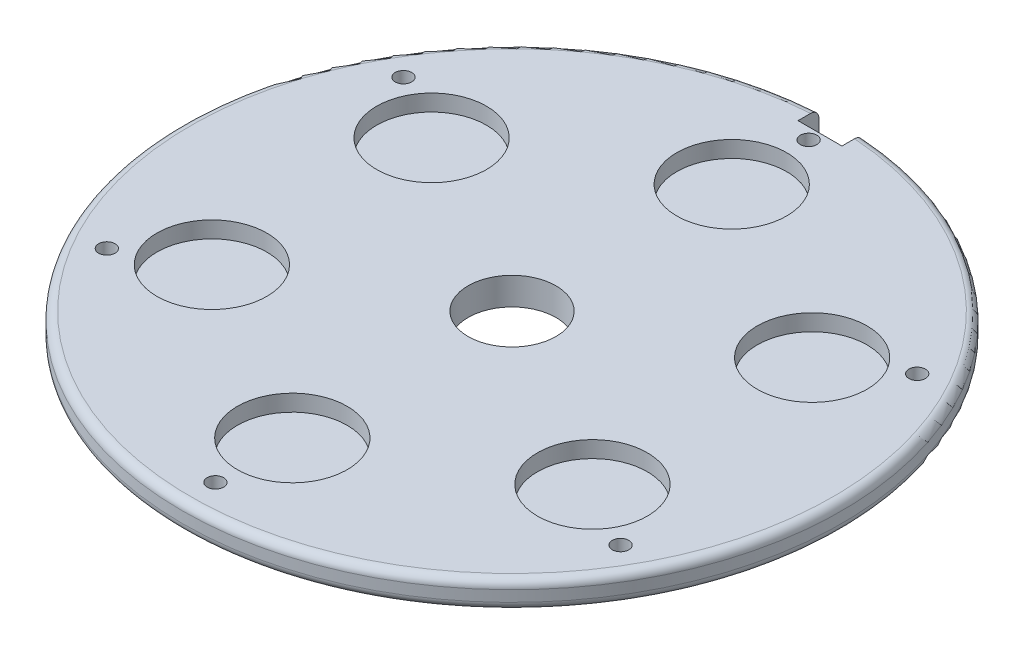
SolidWorks part; units mm, degrees
material "ABS"
ref_plane "Front Plane" through (0, 0, 0) normal (0, 0, 1) x (1, 0, 0)
ref_plane "Top Plane" through (0, 0, 0) normal (0, 1, 0) x (1, 0, 0)
ref_plane "Right Plane" through (0, 0, 0) normal (1, 0, 0) x (0, 0, -1)
sketch "Sketch2" plane through (0, 0, 0) normal (0, 1, 0) x (1, 0, 0)
  circle A0 centre (0, 0) radius 60
  dimension "D1" = 120
extrude "Boss-Extrude1" add sketch "Sketch2" along normal blind 5
sketch "Sketch3" plane through (0, 5, 0) normal (0, 1, 0) x (1, 0, 0)
  circle A0 centre (0, 0) radius 8
  dimension "D1" = 16
extrude "Cut-Extrude1" cut sketch "Sketch3" against normal through all
sketch "Sketch4" plane through (0, 5, 0) normal (0, 1, 0) x (1, 0, 0)
  circle A0 centre (0, 40) radius 10
  dimension "D2" = 20
  dimension "D1" = 40
extrude "Cut-Extrude2" cut sketch "Sketch4" against normal blind 3
pattern_circular "CirPattern1" count 6 over 360 about axis through (0, 0, 0) along (0, 1, 0) of "Cut-Extrude2"
sketch "Sketch5" plane through (0, 5, 0) normal (0, 1, 0) x (1, 0, 0)
  circle A0 centre (0, 54) radius 1.5
  dimension "D2" = 3
  dimension "D1" = 54
extrude "Cut-Extrude3" cut sketch "Sketch5" against normal through all
pattern_circular "CirPattern2" count 6 over 360 about axis through (0, 0, 0) along (0, 1, 0) of "Cut-Extrude3"
sketch "Sketch6" plane through (0, 5, 0) normal (0, 1, 0) x (1, 0, 0)
  line L1 (-4, 60.067) -> (4, 60.067)
  line L2 (-4, 60.067) -> (-4, 56.067)
  line L3 (-4, 56.067) -> (4, 56.067)
  line L4 (4, 60.067) -> (4, 56.067)
  line L5 (-4, 60.067) -> (4, 56.067) construction
  line L6 (-4, 56.067) -> (4, 60.067) construction
  point P0 (0, 58.067)
  dimension "D1" = 8
  dimension "D2" = 4
  dimension "D3" = 0
extrude "Cut-Extrude4" cut sketch "Sketch6" against normal through all
fillet "Fillet1" radius 1.5 2 edges at (0, 0, 60) (0, 5, 60)
